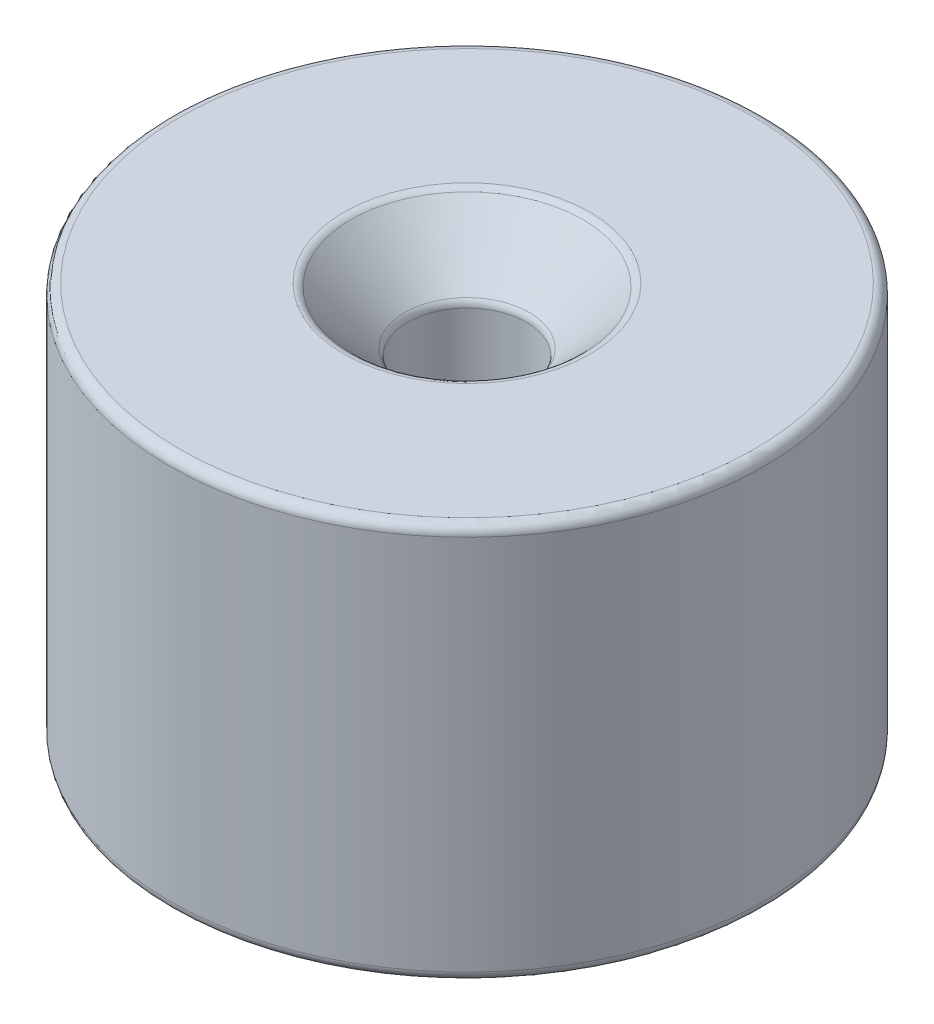
SolidWorks part; units mm, degrees
ref_plane "Front Plane" through (0, 0, 0) normal (0, 0, 1) x (1, 0, 0)
ref_plane "Top Plane" through (0, 0, 0) normal (0, 1, 0) x (1, 0, 0)
ref_plane "Right Plane" through (0, 0, 0) normal (1, 0, 0) x (0, 0, -1)
sketch "Sketch1" plane through (0, 0, 0) normal (0, 1, 0) x (1, 0, 0)
  circle A0 centre (0, 0) radius 15
  circle A1 centre (0, 0) radius 3
  dimension "D1" = 30
  dimension "D2" = 6
extrude "Boss-Extrude1" add sketch "Sketch1" along normal blind 20
chamfer "Chamfer1" distance 3 angle 45 1 edges at (0, 20, 3)
fillet "Fillet1" radius 0.5 5 edges at (0, 0, 15) (0, 0, 3) (0, 17, 3) (0, 20, 15) (0, 20, 6)
